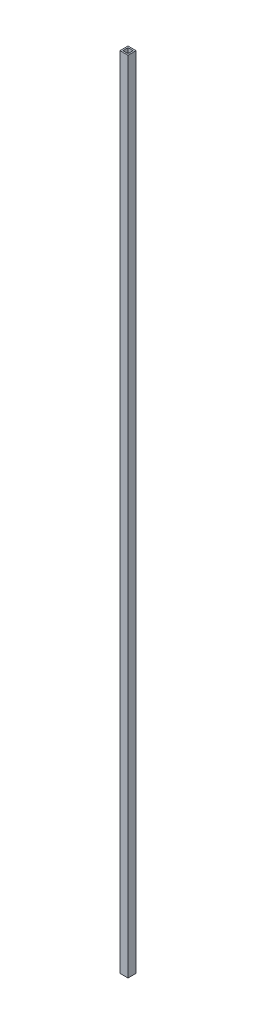
SolidWorks part; units mm, degrees
ref_plane "前视基准面" through (0, 0, 0) normal (0, 0, 1) x (1, 0, 0)
ref_plane "上视基准面" through (0, 0, 0) normal (0, 1, 0) x (1, 0, 0)
ref_plane "右视基准面" through (0, 0, 0) normal (1, 0, 0) x (0, 0, -1)
sketch "草图1" plane through (0, 0, 0) normal (0, 1, 0) x (1, 0, 0)
  line L1 (-3.2, 3.2) -> (3.2, 3.2)
  line L2 (-3.2, 3.2) -> (-3.2, -3.2)
  line L3 (-3.2, -3.2) -> (3.2, -3.2)
  line L4 (3.2, 3.2) -> (3.2, -3.2)
  line L5 (0, -3.2) -> (0, 3.2) construction
  line L6 (-3.2, 0) -> (3.2, 0) construction
  line L7 (-5, 5) -> (5, 5)
  line L8 (-5, 5) -> (-5, -5)
  line L9 (-5, -5) -> (5, -5)
  line L10 (5, 5) -> (5, -5)
  line L11 (0, -5) -> (0, 5) construction
  line L12 (-5, 0) -> (5, 0) construction
  point P0 (0, 0)
  point P4 (0, 0)
  dimension "D1" = 10
  dimension "D2" = 10
  dimension "D3" = 1.8
  dimension "D4" = 1.8
extrude "凸台-拉伸1" add sketch "草图1" along normal blind 1000
